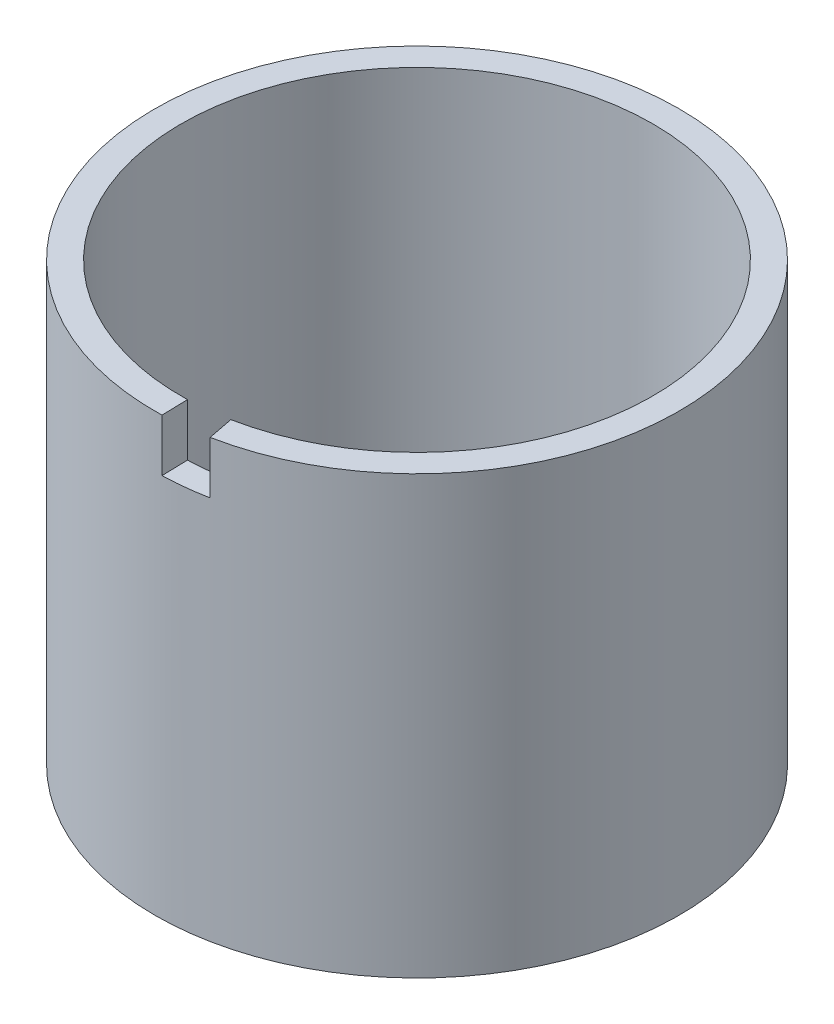
SolidWorks part; units mm, degrees
ref_plane "Front Plane" through (0, 0, 0) normal (0, 0, 1) x (1, 0, 0)
ref_plane "Top Plane" through (0, 0, 0) normal (0, 1, 0) x (1, 0, 0)
ref_plane "Right Plane" through (0, 0, 0) normal (1, 0, 0) x (0, 0, -1)
sketch "Sketch1" plane through (0, 0, 0) normal (0, 1, 0) x (1, 0, 0)
  circle A0 centre (0, 0) radius 15
  dimension "D1" = 30
extrude "Boss-Extrude1" add sketch "Sketch1" along normal blind 25
shell "Shell2" thickness 1.5
sketch "Sketch2" plane through (0, 25, 0) normal (0, 1, 0) x (1, 0, 0)
  line L0 (0.3562, -13.4953) -> (0.3958, -14.9948)
  line L1 (2.5909, -13.2491) -> (2.8787, -14.7212)
  arc A0 (0.3562, -13.4953) -> (2.5909, -13.2491) centre (0, 0) ccw
  arc A1 (0.3958, -14.9948) -> (2.8787, -14.7212) centre (0, 0) ccw
extrude "Cut-Extrude1" cut sketch "Sketch2" against normal blind 3
